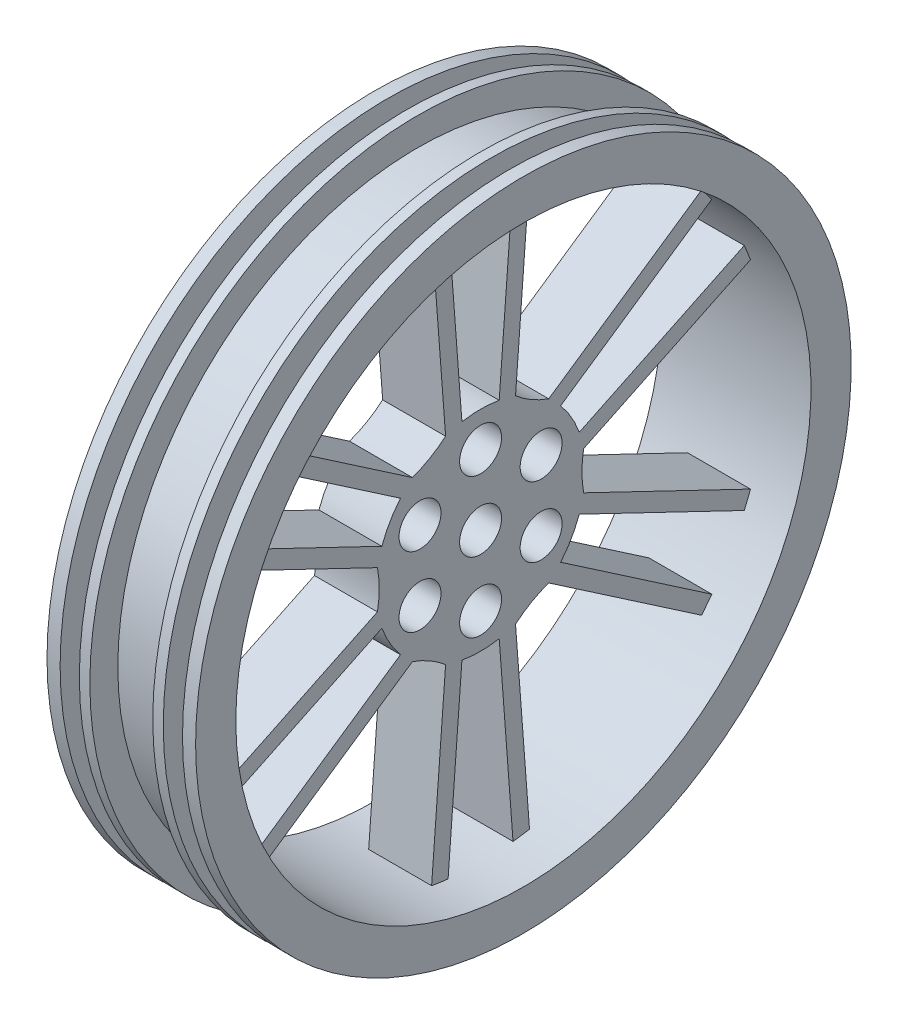
SolidWorks part; units mm, degrees
material "ABS"
ref_plane "Front Plane" through (0, 0, 0) normal (0, 0, 1) x (1, 0, 0)
ref_plane "Top Plane" through (0, 0, 0) normal (0, 1, 0) x (1, 0, 0)
ref_plane "Right Plane" through (0, 0, 0) normal (1, 0, 0) x (0, 0, -1)
sketch "Front" plane through (0, 0, 0) normal (0, 0, 1) x (1, 0, 0)
  line L0 (0, 0) -> (0, 50000) construction
  line L1 (0, 0) -> (50000, 0) construction
sketch "Top" plane through (0, 0, 0) normal (0, 1, 0) x (1, 0, 0)
  line L0 (0, 0) -> (0, 23493.7804) construction
  line L1 (0, 0) -> (23493.7804, 0) construction
  line L2 (-8.5, 32.9) -> (-8.5, 37.5)
  line L3 (-8.5, 37.5) -> (-7, 37.5)
  line L4 (-7, 37.5) -> (-7, 34.3)
  line L5 (-7, 34.3) -> (-4.8, 34.3)
  line L6 (-4.8, 34.3) -> (-4.8, 37.5)
  line L7 (-4.8, 37.5) -> (-3.6, 37.5)
  line L8 (-3.6, 37.5) -> (-3.6, 34.3)
  line L9 (-3.6, 34.3) -> (3.6, 34.3)
  line L10 (-8.5, 32.9) -> (8.5, 32.9)
  line L11 (3.6, 37.5) -> (3.6, 34.3)
  line L12 (4.8, 37.5) -> (3.6, 37.5)
  line L13 (4.8, 34.3) -> (4.8, 37.5)
  line L14 (7, 34.3) -> (4.8, 34.3)
  line L15 (7, 37.5) -> (7, 34.3)
  line L16 (8.5, 37.5) -> (7, 37.5)
  line L17 (8.5, 32.9) -> (8.5, 37.5)
  point P15 (0, 32.9)
  point P17 (0, 34.3)
  dimension "D1" = 75
  dimension "D2" = 17
  dimension "D3" = 2.2
  dimension "D4" = 1.5
  dimension "D5" = 1.2
  dimension "D6" = 3.2
  dimension "D7" = 4.6
sketch "Right" plane through (0, 0, 0) normal (1, 0, 0) x (0, 0, -1)
  line L0 (0, 0) -> (0, 50000) construction
  line L1 (0, 0) -> (50000, 0) construction
revolve "Base" add sketch "Top" angle 360 about L1
sketch "Sketch1" plane through (0, 0, 0) normal (1, 0, 0) x (0, 0, -1)
  line L0 (0, 0) -> (50000, 0) construction
  line L1 (0, 0) -> (0, 50000) construction
  line L2 (0, 0) -> (-35355.3391, 35355.3391) construction
  line L3 (-2.1321, 11.8091) -> (-3.715, 32.6896)
  line L4 (-4, 11.3137) -> (-5.6, 32.4199)
  line L5 (4, 11.3137) -> (5.6, 32.4199)
  line L6 (2.1321, 11.8091) -> (3.715, 32.6896)
  line L7 (7.798, 9.121) -> (25.2765, 21.0597)
  line L8 (9.1609, 7.751) -> (26.4525, 19.5621)
  line L9 (11.293, 4.0581) -> (30.1675, 13.1275)
  line L10 (11.798, 2.1928) -> (30.8765, 11.3602)
  line L11 (11.798, -2.1928) -> (30.8765, -11.3602)
  line L12 (11.293, -4.0581) -> (30.1675, -13.1275)
  line L13 (9.1609, -7.751) -> (26.4525, -19.5621)
  line L14 (7.798, -9.121) -> (25.2765, -21.0597)
  line L15 (4, -11.3137) -> (5.6, -32.4199)
  line L16 (2.1321, -11.8091) -> (3.715, -32.6896)
  line L17 (-2.1321, -11.8091) -> (-3.715, -32.6896)
  line L18 (-4, -11.3137) -> (-5.6, -32.4199)
  line L19 (-7.798, -9.121) -> (-25.2765, -21.0597)
  line L20 (-9.1609, -7.751) -> (-26.4525, -19.5621)
  line L21 (-11.293, -4.0581) -> (-30.1675, -13.1275)
  line L22 (-11.798, -2.1928) -> (-30.8765, -11.3602)
  line L23 (-11.798, 2.1928) -> (-30.8765, 11.3602)
  line L24 (-11.293, 4.0581) -> (-30.1675, 13.1275)
  line L25 (-9.1609, 7.751) -> (-26.4525, 19.5621)
  line L26 (-7.798, 9.121) -> (-25.2765, 21.0597)
  circle A0 centre (0, 0) radius 12 construction
  circle A1 centre (0, 8) radius 2.4
  circle A2 centre (0, 0) radius 2.4
  circle A3 centre (0, 0) radius 32.9 construction
  circle A4 centre (-6.9282, 4) radius 2.4
  circle A5 centre (-6.9282, -4) radius 2.4
  circle A6 centre (0, -8) radius 2.4
  circle A7 centre (6.9282, -4) radius 2.4
  circle A8 centre (6.9282, 4) radius 2.4
  circle A9 centre (0, 0) radius 32.9 construction
  arc A10 (-5.6, 32.4199) -> (-3.715, 32.6896) centre (0, 0) cw
  arc A11 (5.6, 32.4199) -> (3.715, 32.6896) centre (0, 0) ccw
  arc A12 (25.2765, 21.0597) -> (26.4525, 19.5621) centre (0, 0) cw
  arc A13 (30.8765, 11.3602) -> (30.1675, 13.1275) centre (0, 0) ccw
  arc A14 (30.8765, -11.3602) -> (30.1675, -13.1275) centre (0, 0) cw
  arc A15 (25.2765, -21.0597) -> (26.4525, -19.5621) centre (0, 0) ccw
  arc A16 (5.6, -32.4199) -> (3.715, -32.6896) centre (0, 0) cw
  arc A17 (-5.6, -32.4199) -> (-3.715, -32.6896) centre (0, 0) ccw
  arc A18 (-25.2765, -21.0597) -> (-26.4525, -19.5621) centre (0, 0) cw
  arc A19 (-30.8765, -11.3602) -> (-30.1675, -13.1275) centre (0, 0) ccw
  arc A20 (-30.8765, 11.3602) -> (-30.1675, 13.1275) centre (0, 0) cw
  arc A21 (-25.2765, 21.0597) -> (-26.4525, 19.5621) centre (0, 0) ccw
  arc A22 (-2.1321, 11.8091) -> (2.1321, 11.8091) centre (0, 0) cw
  arc A23 (-4, 11.3137) -> (-7.798, 9.121) centre (-11.798, 20.4347) cw
  arc A24 (7.798, 9.121) -> (4, 11.3137) centre (11.798, 20.4347) cw
  arc A25 (9.1609, 7.751) -> (11.293, 4.0581) centre (0, 0) cw
  arc A26 (11.798, -2.1928) -> (11.798, 2.1928) centre (23.5959, 0) cw
  arc A27 (11.293, -4.0581) -> (9.1609, -7.751) centre (0, 0) cw
  arc A28 (4, -11.3137) -> (7.798, -9.121) centre (11.798, -20.4347) cw
  arc A29 (2.1321, -11.8091) -> (-2.1321, -11.8091) centre (0, 0) cw
  arc A30 (-7.798, -9.121) -> (-4, -11.3137) centre (-11.798, -20.4347) cw
  arc A31 (-9.1609, -7.751) -> (-11.293, -4.0581) centre (0, 0) cw
  arc A32 (-11.798, 2.1928) -> (-11.798, -2.1928) centre (-23.5959, 0) cw
  arc A33 (-11.293, 4.0581) -> (-9.1609, 7.751) centre (0, 0) cw
  point P14 (0, -10.4)
  point P24 (0, 0)
  point P25 (0, 10.4)
  point P78 (0, 0)
  point P105 (0, 0)
  dimension "D1" = 24
  dimension "D3" = 4.8
  dimension "D4" = 4.8
  dimension "D2" = 45
  dimension "D6" = 20.8
  dimension "D7" = 1.9
  dimension "D8" = 11.2
  dimension "D9" = 8
  dimension "D5" = 6
  dimension "D10" = 6
  dimension "D11" = 6
extrude "Boss-Extrude1" add sketch "Sketch1" along normal mid plane 7.2
